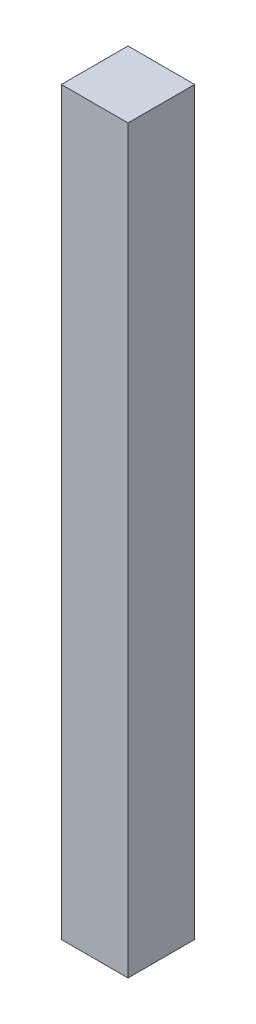
SolidWorks part; units mm, degrees
ref_plane "Front Plane" through (0, 0, 0) normal (0, 0, 1) x (1, 0, 0)
ref_plane "Top Plane" through (0, 0, 0) normal (0, 1, 0) x (1, 0, 0)
ref_plane "Right Plane" through (0, 0, 0) normal (1, 0, 0) x (0, 0, -1)
other "Configuration Table"
sketch "Sketch1" plane through (0, 0, 0) normal (0, 0, 1) x (1, 0, 0)
  line L1 (637, 230) -> (655, 230)
  line L2 (637, 230) -> (637, 430)
  line L3 (637, 430) -> (655, 430)
  line L4 (655, 230) -> (655, 430)
extrude "TOPPING_klape_alt2_gazli_amortisor_2_1" add sketch "Sketch1" along normal blind 18 from offset 8 separate body
